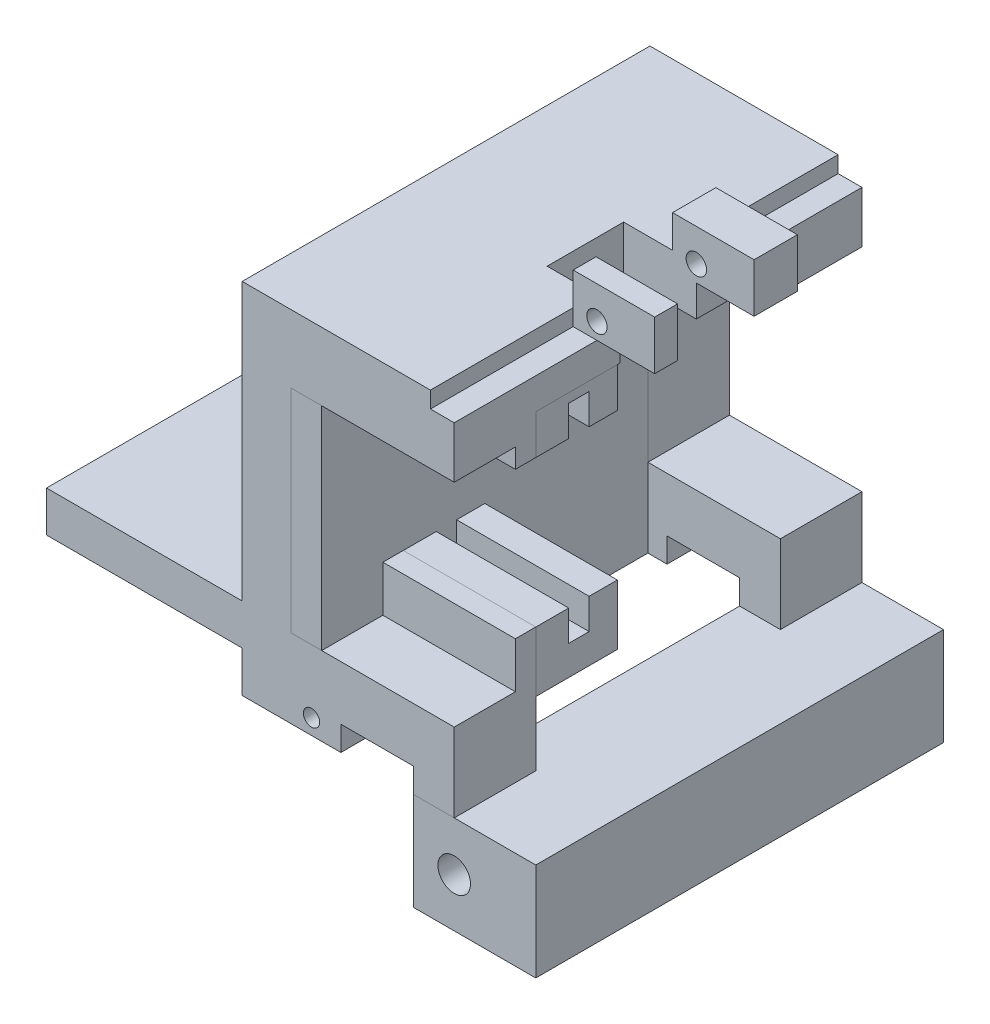
SolidWorks part; units mm, degrees
material "ABS"
ref_plane "Front Plane" through (0, 0, 0) normal (0, 0, 1) x (1, 0, 0)
ref_plane "Top Plane" through (0, 0, 0) normal (0, 1, 0) x (1, 0, 0)
ref_plane "Right Plane" through (0, 0, 0) normal (1, 0, 0) x (0, 0, -1)
sketch "Sketch8" plane through (0, 0, 0) normal (0, 0, 1) x (1, 0, 0)
  line L0 (0, 0) -> (0, 48.6918)
  line L1 (0, 48.6918) -> (-33.02, 48.6918)
  line L2 (-33.02, 48.6918) -> (-33.02, 5.588)
  line L3 (-33.02, 5.588) -> (-63.5, 5.588)
  line L4 (-63.5, 5.588) -> (-63.5, -0.762)
  line L5 (-63.5, -0.762) -> (-33.02, -0.762)
  line L6 (-33.02, -0.762) -> (-33.02, -9.525)
  line L8 (-33.02, -9.525) -> (-9.525, -9.525)
  line L11 (0, 0) -> (0, -9.525)
  line L12 (0, -9.525) -> (-9.525, -9.525)
  circle A0 centre (-15.875, 28.5877) radius 1.27
  circle A1 centre (-22.225, -4.7625) radius 1.27
  dimension "D7" = 2.54
  dimension "D8" = 22.225
  dimension "D9" = 2.54
  dimension "D1" = 30.48
  dimension "D2" = 33.02
  dimension "D3" = 48.6918
  dimension "D4" = 43.1038
  dimension "D5" = 6.35
  dimension "D6" = 23.495
extrude "Boss-Extrude3" add sketch "Sketch8" along normal blind 101.6
sketch "Sketch40" plane through (0, -9.525, 0) normal (0, -1, 0) x (1, 0, 0)
  line L0 (0, 0) -> (0, 31.75) construction
  line L1 (0, 101.6) -> (0, 0) construction
  line L2 (0, 31.75) -> (-25.4, 31.75)
  line L3 (-25.4, 31.75) -> (-25.4, 69.85)
  line L4 (-25.4, 69.85) -> (0, 69.85)
  line L5 (0, 69.85) -> (0, 31.75)
extrude "Cut-Extrude24" cut sketch "Sketch40" against normal blind 50.8
sketch "Sketch18" plane through (0, 0, 101.6) normal (0, 0, 1) x (1, 0, 0)
  line L0 (-33.02, -9.525) -> (-33.02, -7.1628)
  line L1 (-33.02, -0.762) -> (-33.02, -9.525) construction
  line L3 (-33.02, -7.1628) -> (0, -7.1628)
  line L4 (0, 48.6918) -> (0, -9.525) construction
  line L5 (0, -7.1628) -> (0, -9.525)
  line L6 (0, -9.525) -> (-33.02, -9.525)
extrude "Cut-Extrude11" cut sketch "Sketch18" against normal blind 101.6 and the other way through all
sketch "Sketch19" plane through (0, 0, 0) normal (0, 0, -1) x (-1, 0, 0)
  line L0 (3.7065, 48.6918) -> (3.7065, 53.7718)
  line L1 (0, 48.6918) -> (33.02, 48.6918) construction
  line L2 (3.7065, 53.7718) -> (-8.9935, 53.7718)
  line L3 (-8.9935, 53.7718) -> (-8.9935, 46.1359)
  line L6 (-8.9935, 46.1359) -> (0, 46.1359)
  circle A0 centre (22.225, -4.7625) radius 1.27 construction
  circle A1 centre (0, 48.6918) radius 1.5875
  point P0 (23.495, -4.759)
  point P1 (23.495, -4.766)
  point P4 (22.225, -4.7625)
  dimension "D1" = 3.175
  dimension "D2" = 5.08
sketch "Sketch20" plane through (0, 0, 101.6) normal (0, 0, 1) x (1, 0, 0)
  circle A0 centre (0, 48.6918) radius 1.5875
  dimension "D1" = 3.175
extrude "Boss-Extrude4" add sketch "Sketch19" against normal blind 101.6
extrude "Cut-Extrude12" cut sketch "Sketch20" against normal blind 101.6
sketch "Sketch21" plane through (0, -7.1628, 0) normal (0, -1, 0) x (1, 0, 0)
  line L28 (-33.02, 101.6) -> (0, 101.6)
  line L29 (0, 101.6) -> (0, 82.55)
  line L30 (0, 101.6) -> (0, 69.85) construction
  line L31 (0, 82.55) -> (-33.02, 82.55)
  line L32 (-33.02, 101.6) -> (-33.02, 0) construction
  line L33 (-33.02, 82.55) -> (-33.02, 101.6)
  line L34 (-33.02, 0) -> (-33.02, 19.05)
  line L35 (-33.02, 19.05) -> (0, 19.05)
  line L36 (0, 31.75) -> (0, 0) construction
  line L37 (0, 19.05) -> (0, 0)
  line L38 (0, 0) -> (-33.02, 0)
extrude "Cut-Extrude13" cut sketch "Sketch21" against normal through all
sketch "Sketch24" plane through (0, 53.7718, 0) normal (0, 1, 0) x (1, 0, 0)
  line L11 (8.9935, -101.6) -> (8.9935, 0) construction
  line L20 (0, -82.55) -> (8.9935, -82.55)
  line L21 (8.9935, -82.55) -> (8.9935, -101.6)
  line L22 (8.9935, -101.6) -> (0, -101.6)
  line L23 (0, -101.6) -> (0, -82.55)
  line L24 (0, 0) -> (8.9935, 0)
  line L25 (8.9935, 0) -> (8.9935, -19.05)
  line L26 (8.9935, -19.05) -> (0, -19.05)
  line L27 (0, -19.05) -> (0, 0)
extrude "Cut-Extrude15" cut sketch "Sketch24" against normal through all
sketch "Sketch38" plane through (8.9935, 0, 0) normal (1, 0, 0) x (0, 0, -1)
  line L10 (-50.8, 53.7718) -> (-44.8437, 53.7718) construction
  line L16 (-56.7563, 53.7718) -> (-56.7563, 46.1359)
  line L18 (-82.55, 46.1359) -> (-19.05, 46.1359) construction
  line L20 (-82.55, 53.7718) -> (-19.05, 53.7718) construction
  line L22 (-50.8, 53.7718) -> (-56.7563, 53.7718) construction
  line L27 (-56.7563, 53.7718) -> (-44.8437, 53.7718)
  line L28 (-44.8437, 53.7718) -> (-44.8437, 46.1359)
  line L29 (-56.7563, 46.1359) -> (-44.8437, 46.1359)
extrude "Cut-Extrude21" cut sketch "Sketch38" against normal blind 20.32
sketch "Sketch41" plane through (0, 5.588, 0) normal (0, 1, 0) x (1, 0, 0)
  line L9 (-63.5, 0) -> (-33.02, 0)
  line L10 (-33.02, 0) -> (-33.02, -19.05)
  line L11 (-33.02, -19.05) -> (-33.02, 0) construction
  line L12 (-33.02, -19.05) -> (-63.5, -19.05)
  line L13 (-63.5, -101.6) -> (-63.5, 0) construction
  line L14 (-63.5, -19.05) -> (-63.5, 0)
  line L15 (-33.02, -101.6) -> (-63.5, -101.6)
  line L16 (-63.5, -101.6) -> (-63.5, -82.55)
  line L17 (-63.5, -82.55) -> (-33.02, -82.55)
  line L18 (-33.02, -82.55) -> (-33.02, -19.05) construction
  line L19 (-33.02, -101.6) -> (-33.02, -82.55) construction
  line L20 (-33.02, -82.55) -> (-33.02, -101.6)
extrude "Cut-Extrude25" cut sketch "Sketch41" against normal through all
sketch "Sketch42" plane through (0, 0, 69.85) normal (0, 0, -1) x (-1, 0, 0)
  line L0 (15.875, 28.5877) -> (15.875, 38.1127) construction
  line L1 (15.875, 38.1127) -> (0, 38.1127) construction
  line L2 (0, 41.275) -> (0, -7.1628) construction
sketch "Sketch43" plane through (0, 0, 0) normal (1, 0, 0) x (0, 0, -1)
  line L1 (-82.55, -7.1628) -> (-69.85, -7.1628) construction
  line L6 (-69.85, 38.1127) -> (-69.85, 5.0927)
  line L7 (-69.85, 41.275) -> (-69.85, -7.1628) construction
  line L8 (-69.85, 5.0927) -> (-82.55, 5.0927)
  line L9 (-82.55, 46.1359) -> (-82.55, -7.1628) construction
  line L10 (-82.55, 5.0927) -> (-82.55, 38.1127)
  line L11 (-82.55, 38.1127) -> (-69.85, 38.1127)
  point P11 (0, 0)
  point P12 (0, 0)
  dimension "D1" = 12.2555
extrude "Cut-Extrude26" cut sketch "Sketch43" against normal blind 25.4
sketch "Sketch44" plane through (-25.4, 0, 0) normal (1, 0, 0) x (0, 0, -1)
  line L1 (-69.85, 35.0901) -> (-69.85, 38.1127)
  line L4 (-69.85, 12.2428) -> (-69.85, 5.0927)
  line L11 (-69.85, 38.1127) -> (-73.025, 38.1127)
  line L12 (-69.85, 38.1127) -> (-82.55, 38.1127) construction
  line L13 (-73.025, 38.1127) -> (-73.025, 35.0901)
  line L14 (-73.025, 35.0901) -> (-69.85, 35.0901)
  line L15 (-69.85, 5.0927) -> (-69.85, -7.1628) construction
  line L18 (-69.85, 12.2428) -> (-73.025, 12.2428)
  line L19 (-73.025, 12.2428) -> (-73.025, 5.0927)
  line L20 (-82.55, 5.0927) -> (-69.85, 5.0927) construction
  line L21 (-73.025, 5.0927) -> (-69.85, 5.0927)
extrude "Boss-Extrude5" add sketch "Sketch44" along normal blind 25.4
sketch "Sketch45" plane through (-25.4, 0, 0) normal (1, 0, 0) x (0, 0, -1)
  line L1 (-69.85, 41.275) -> (-31.75, 41.275) construction
  line L4 (-69.85, 41.275) -> (-69.85, 35.0901) construction
  line L7 (-57.15, 12.2301) -> (-57.15, 2.8575)
  line L8 (-57.15, 2.8575) -> (-69.85, 2.8575)
  line L18 (-69.85, 12.2301) -> (-64.7192, 12.2301)
  line L19 (-69.85, 35.0901) -> (-64.7192, 35.0901)
  line L21 (-69.85, 41.275) -> (-57.15, 41.275)
  line L25 (-69.85, 28.575) -> (-69.85, 39.8526) construction
  line L26 (-64.7192, 35.0901) -> (-64.7192, 39.8526)
  line L27 (-64.7192, 39.8526) -> (-61.5442, 39.8526)
  line L28 (-61.5442, 39.8526) -> (-61.5442, 35.0901)
  line L29 (-61.5442, 35.0901) -> (-57.15, 35.0901)
  line L30 (-57.15, 35.0901) -> (-57.15, 41.275)
  line L31 (-64.7192, 12.2301) -> (-64.7192, 7.4676)
  line L32 (-64.7192, 7.4676) -> (-61.5442, 7.4676)
  line L33 (-61.5442, 7.4676) -> (-61.5442, 12.2301)
  line L34 (-61.5442, 12.2301) -> (-57.15, 12.2301)
  line L35 (-69.85, 2.8575) -> (-69.85, 12.2301)
  dimension "D5" = 9.3726
  dimension "D6" = 12.7
  dimension "D9" = 12.7
extrude "Boss-Extrude6" add sketch "Sketch45" along normal blind 25.4 separate body
sketch "Sketch46" plane through (0, 0, 82.55) normal (0, 0, 1) x (1, 0, 0)
  line L0 (0, 48.6918) -> (0, -14.8082) construction
  line L1 (0, -7.1628) -> (12.7, -7.1628)
  line L2 (12.7, -7.1628) -> (12.7, -22.4028)
  line L3 (12.7, -22.4028) -> (-6.35, -22.4028)
  line L4 (-6.35, -22.4028) -> (-6.35, -7.1628)
  line L6 (-33.02, -7.1628) -> (0, -7.1628) construction
  circle A0 centre (0, -14.8082) radius 2.54
  dimension "D1" = 5.08
extrude "Boss-Extrude7" add sketch "Sketch46" against normal blind 63.5 separate body
sketch "Sketch48" plane through (0, 0, 82.55) normal (0, 0, 1) x (1, 0, 0)
  line L0 (-17.653, -7.1628) -> (-17.653, -3.3468)
  line L1 (-33.02, -7.1628) -> (0, -7.1628) construction
  line L2 (-17.653, -3.3468) -> (-6.35, -3.3468)
  line L3 (-6.35, -3.3468) -> (-6.35, -7.1628)
extrude "Cut-Extrude29" cut sketch "Sketch48" against normal blind 12.7 and the other way through all flip side to cut
sketch "Sketch49" plane through (0, 0, 19.05) normal (0, 0, -1) x (-1, 0, 0)
  line L0 (22.225, -4.7625) -> (12.573, -4.7625) construction
  line L1 (17.653, -7.1628) -> (17.653, -3.3528)
  line L2 (0, -7.1628) -> (33.02, -7.1628) construction
  line L3 (17.653, -3.3528) -> (6.35, -3.3528)
  line L4 (6.35, -3.3528) -> (6.35, -7.1628)
  line L5 (6.35, -7.1628) -> (17.653, -7.1628)
extrude "Cut-Extrude31" cut sketch "Sketch49" against normal blind 12.7
sketch "Sketch50" plane through (0, 46.1359, 0) normal (0, 1, 0) x (1, 0, 0)
  line L4 (-11.3265, -56.7563) -> (-11.3265, -44.8437)
  line L5 (-11.3265, -44.8437) -> (0, -44.8437)
  line L6 (0, -44.8437) -> (0, -56.7563)
  line L7 (0, -56.7563) -> (-11.3265, -56.7563)
extrude "Cut-Extrude33" cut sketch "Sketch50" against normal blind 4.8768
sketch "Sketch52" plane through (-25.4, 0, 0) normal (1, 0, 0) x (0, 0, -1)
  line L22 (-73.025, 38.1127) -> (-82.55, 38.1127)
  line L31 (-82.55, 38.1127) -> (-82.55, 5.0927)
  line L32 (-82.55, 5.0927) -> (-73.025, 5.0927)
  line L35 (-82.55, 5.0927) -> (-73.025, 5.0927) construction
  line L37 (-73.025, 5.0927) -> (-73.025, 12.2428)
  line L43 (-73.025, 12.2428) -> (-64.7192, 12.2301)
  line L46 (-64.7192, 12.2301) -> (-64.7192, 7.4676)
  line L77 (-64.7192, 7.4676) -> (-61.5442, 7.4676)
  line L78 (-64.7192, 7.4676) -> (-61.5442, 7.4676) construction
  line L79 (-61.5442, 7.4676) -> (-61.5442, 12.2301)
  line L80 (-61.5442, 12.2301) -> (-57.15, 12.2301)
  line L81 (-57.15, 12.2301) -> (-57.15, 2.8575)
  line L82 (-57.15, 2.8575) -> (-69.85, 2.8575)
  line L83 (-69.85, 2.8575) -> (-69.85, -7.1628)
  line L84 (-69.85, -7.1628) -> (-31.75, -7.1628)
  line L85 (-31.75, -7.1628) -> (-31.75, 41.275)
  line L86 (-31.75, 41.275) -> (-57.15, 41.275)
  line L87 (-57.15, 41.275) -> (-57.15, 35.0901)
  line L88 (-57.15, 35.0901) -> (-61.5442, 35.0901)
  line L89 (-61.5442, 35.0901) -> (-61.5442, 39.8526)
  line L90 (-61.5442, 39.8526) -> (-64.7192, 39.8526)
  line L91 (-64.7192, 39.8526) -> (-61.5442, 39.8526) construction
  line L92 (-64.7192, 39.8526) -> (-64.7192, 35.0901)
  line L93 (-64.7192, 35.0901) -> (-73.025, 35.0901)
  line L94 (-73.025, 35.0901) -> (-73.025, 38.1127)
extrude "Boss-Extrude8" add sketch "Sketch52" along normal blind 4.7625 separate body
sketch "Sketch53" plane through (8.9935, 0, 0) normal (1, 0, 0) x (0, 0, -1)
  line L0 (-82.55, 53.7718) -> (-82.55, 46.1359) construction
  line L1 (-82.55, 46.1359) -> (-60.325, 46.1359) construction
  line L2 (-82.55, 46.1359) -> (-56.7563, 46.1359) construction
  line L3 (-60.325, 46.1359) -> (-60.325, 53.7718) construction
  line L4 (-82.55, 53.7718) -> (-56.7563, 53.7718) construction
  line L5 (-60.325, 53.7718) -> (-82.55, 53.7718) construction
  line L6 (-60.325, 53.7718) -> (-60.325, 46.1359)
  line L7 (-60.325, 46.1359) -> (-82.55, 46.1359)
  line L8 (-82.55, 46.1359) -> (-82.55, 53.7718)
  line L9 (-82.55, 53.7718) -> (-60.325, 53.7718)
extrude "Cut-Extrude34" cut sketch "Sketch53" against normal blind 12.7
sketch "Sketch54" plane through (8.9935, 0, 0) normal (1, 0, 0) x (0, 0, -1)
  line L0 (-19.05, 53.7718) -> (-38.1, 53.7718)
  line L1 (-44.8437, 53.7718) -> (-19.05, 53.7718) construction
  line L2 (-38.1, 53.7718) -> (-38.1, 46.1359)
  line L3 (-44.8437, 46.1359) -> (-19.05, 46.1359) construction
  line L4 (-38.1, 46.1359) -> (-19.05, 46.1359)
  line L5 (-19.05, 46.1359) -> (-19.05, 53.7718)
extrude "Cut-Extrude35" cut sketch "Sketch54" against normal blind 12.7
sketch "Sketch56" plane through (0, 0, 0) normal (1, 0, 0) x (0, 0, -1)
  line L0 (-31.75, -7.1628) -> (-31.75, 5.0927) construction
  line L1 (-31.75, 41.275) -> (-31.75, -7.1628) construction
  line L2 (-31.75, 5.0927) -> (-19.05, 5.0927)
  line L3 (-19.05, 46.1359) -> (-19.05, -7.1628) construction
  line L4 (-19.05, 5.0927) -> (-19.05, 38.1127)
  line L5 (-19.05, 38.1127) -> (-31.75, 38.1127)
  line L6 (-31.75, 38.1127) -> (-31.75, 5.0927)
extrude "Cut-Extrude36" cut sketch "Sketch56" against normal blind 20.6375
